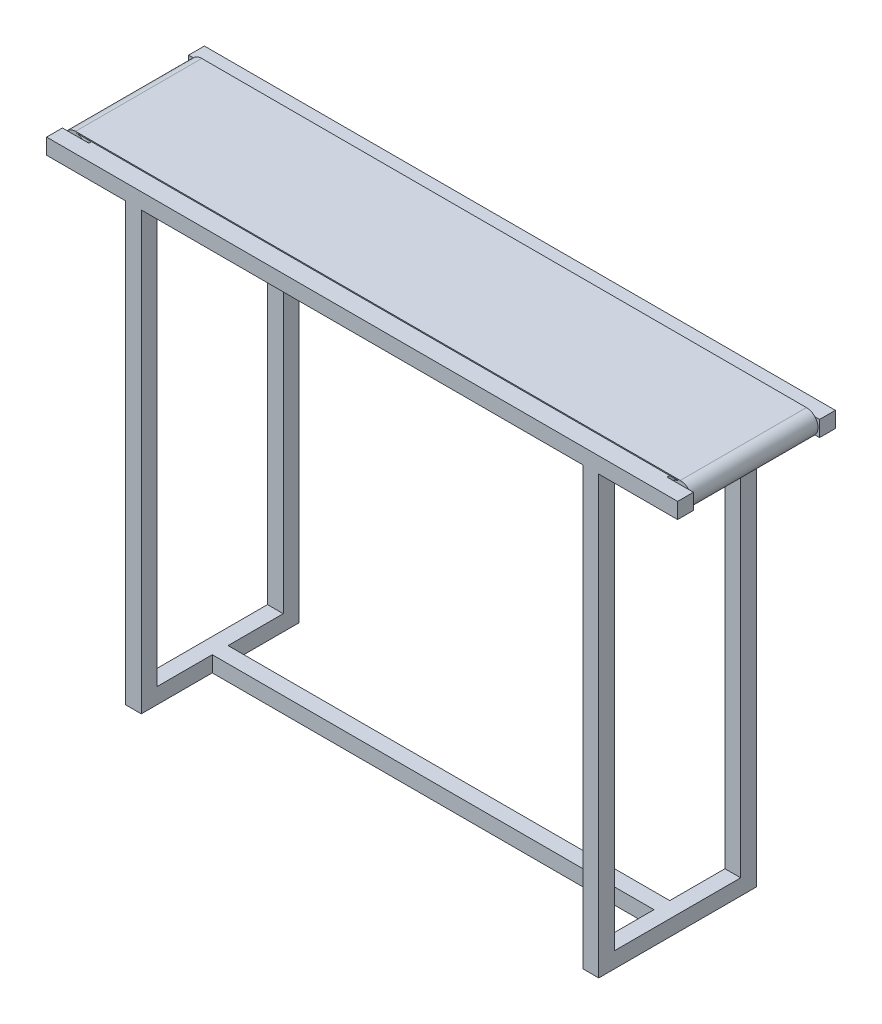
SolidWorks part; units mm, degrees
ref_plane "Front Plane" through (0, 0, 0) normal (0, 0, 1) x (1, 0, 0)
ref_plane "Top Plane" through (0, 0, 0) normal (0, 1, 0) x (1, 0, 0)
ref_plane "Right Plane" through (0, 0, 0) normal (1, 0, 0) x (0, 0, -1)
sketch "Sketch1" plane through (0, 0, 0) normal (0, 0, 1) x (1, 0, 0)
  line L0 (0, 0) -> (0, 800)
  line L1 (0, 800) -> (-150, 800)
  line L2 (-150, 800) -> (-150, 830)
  line L3 (-150, 830) -> (1050, 830)
  line L4 (1050, 830) -> (1050, 800)
  line L5 (1050, 800) -> (900, 800)
  line L6 (900, 800) -> (900, 0)
  line L7 (900, 0) -> (870, 0)
  line L8 (870, 0) -> (870, 800)
  line L9 (870, 800) -> (30, 800)
  line L10 (30, 800) -> (30, 0)
  line L11 (30, 0) -> (0, 0)
  point P13 (-150, 815)
  dimension "D1" = 30
  dimension "D2" = 30
  dimension "D3" = 30
  dimension "D4" = 1200
  dimension "D5" = 150
  dimension "D6" = 150
  dimension "D7" = 800
extrude "Boss-Extrude1" add sketch "Sketch1" along normal blind 30
sketch "Sketch2" plane through (0, 0, 0) normal (0, -1, 0) x (1, 0, 0)
  line L1 (0, 0) -> (30, 0)
  line L2 (0, 0) -> (0, 300)
  line L3 (0, 300) -> (30, 300)
  line L4 (30, 0) -> (30, 300)
  line L5 (900, 0) -> (870, 0)
  line L6 (900, 0) -> (900, 300)
  line L7 (900, 300) -> (870, 300)
  line L8 (870, 0) -> (870, 300)
  point P10 (885, 0)
  dimension "D1" = 30
  dimension "D2" = 30
  dimension "D3" = 300
  dimension "D4" = 300
extrude "Boss-Extrude2" add sketch "Sketch2" along normal blind 30
sketch "Sketch3" plane through (0, 0, 0) normal (0, 1, 0) x (1, 0, 0)
  line L0 (30, -30) -> (30, -300) construction
  line L1 (0, -300) -> (30, -300)
  line L2 (0, -300) -> (0, -270)
  line L3 (0, -270) -> (30, -270)
  line L4 (30, -300) -> (30, -270)
  line L5 (900, -30) -> (900, -300) construction
  line L6 (870, -300) -> (900, -300)
  line L7 (870, -300) -> (870, -270)
  line L8 (870, -270) -> (900, -270)
  line L9 (900, -300) -> (900, -270)
  point P14 (15, -300)
  dimension "D1" = 30
  dimension "D2" = 30
extrude "Boss-Extrude3" add sketch "Sketch3" along normal blind 800
sketch "Sketch4" plane through (0, 800, 0) normal (0, 1, 0) x (1, 0, 0)
  line L0 (0, -300) -> (30, -300) construction
  line L1 (-150, -300) -> (1050, -300)
  line L2 (-150, -300) -> (-150, -270)
  line L3 (-150, -270) -> (1050, -270)
  line L4 (1050, -300) -> (1050, -270)
  dimension "D1" = 1200
  dimension "D2" = 0
  dimension "D3" = 30
extrude "Boss-Extrude4" add sketch "Sketch4" along normal blind 30
sketch "Sketch5" plane through (0, 0, 30) normal (0, 0, 1) x (1, 0, 0)
  line L0 (-150, 830) -> (1050, 830) construction
  line L1 (-100, 830) -> (1000, 830)
  line L2 (-100, 830) -> (-100, 800)
  line L3 (-100, 800) -> (1000, 800)
  line L4 (1000, 830) -> (1000, 800)
  line L5 (900, 800) -> (1050, 800) construction
  line L6 (-150, 830) -> (-150, 800) construction
  line L7 (1050, 830) -> (1050, 800) construction
  dimension "D1" = 50
  dimension "D2" = 50
extrude "Boss-Extrude5" add sketch "Sketch5" along normal up to next
sketch "Sketch6" plane through (30, 0, 0) normal (1, 0, 0) x (0, 0, -1)
  line L0 (-150, 0) -> (-150, -30) construction
  line L1 (-30, 0) -> (-270, 0) construction
  line L2 (0, -30) -> (-300, -30) construction
  line L4 (-165, 0) -> (-135, 0)
  line L5 (-165, 0) -> (-165, -30)
  line L6 (-165, -30) -> (-135, -30)
  line L7 (-135, 0) -> (-135, -30)
  dimension "D1" = 15
  dimension "D2" = 15
extrude "Boss-Extrude6" add sketch "Sketch6" along normal up to next
sketch "Sketch7" plane through (0, 0, 270) normal (0, 0, -1) x (-1, 0, 0)
  line L0 (-1050, 815) -> (150, 815) construction
  line L1 (-1050, 800) -> (-1050, 830) construction
  line L2 (150, 830) -> (150, 800) construction
  circle A0 centre (-1025, 815) radius 20
  circle A1 centre (125, 815) radius 20
  dimension "D1" = 40
  dimension "D4" = 40
  dimension "D2" = 25
  dimension "D3" = 25
extrude "Boss-Extrude9" add sketch "Sketch7" along normal blind 240
sketch "Sketch8" plane through (0, 0, 30) normal (0, 0, -1) x (-1, 0, 0)
  line L0 (125, 835) -> (-1025, 835)
  line L2 (-1025, 795) -> (125, 795)
  line L3 (125, 837) -> (-1025, 837)
  line L4 (-1025, 793) -> (125, 793)
  arc A0 (-1025, 835) -> (-1025, 795) centre (-1025, 815) ccw
  arc A1 (125, 795) -> (125, 835) centre (125, 815) ccw
  arc A2 (-1025, 837) -> (-1025, 793) centre (-1025, 815) ccw
  arc A3 (125, 793) -> (125, 837) centre (125, 815) ccw
  dimension "D1" = 2
extrude "Boss-Extrude10" add sketch "Sketch8" against normal blind 240
sketch "Sketch9" plane through (0, -30, 0) normal (0, -1, 0) x (1, 0, 0)
  line L0 (0, 150) -> (900, 150) construction
  line L1 (0, 300) -> (0, 0) construction
  line L2 (900, 0) -> (900, 300) construction
  line L3 (450, 150) -> (450, 11.4011) construction
  line L4 (15, 300) -> (15, 0) construction
  line L5 (30, 300) -> (0, 300) construction
  line L6 (0, 0) -> (30, 0) construction
  line L7 (30, 300) -> (870, 300) construction
  circle A0 centre (15, 280) radius 6
  circle A1 centre (15, 20) radius 6
  circle A2 centre (885, 20) radius 6
  circle A3 centre (885, 280) radius 6
  dimension "D1" = 12
  dimension "D2" = 20
extrude "Cut-Extrude1" cut sketch "Sketch9" against normal blind 100
